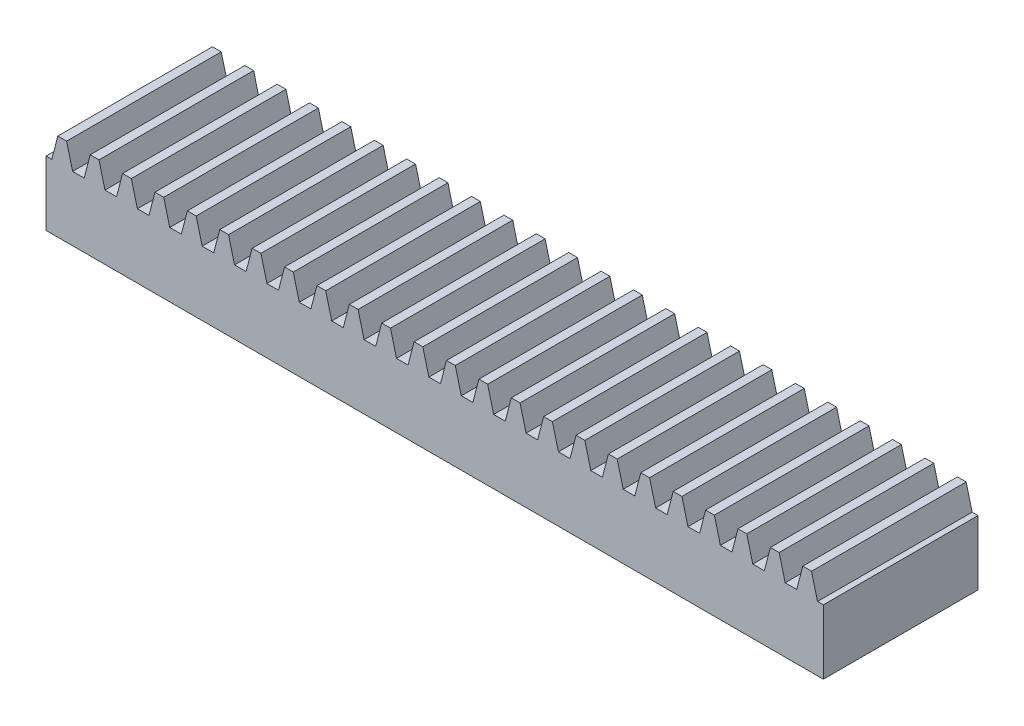
SolidWorks part; units mm, degrees
extrude "Blank" add sketch "BlankSke" against normal blind 30
sketch "BlankSke" plane through (0, 0, 0) normal (0, 0, 1) x (1, 0, 0)
  line L1 (0, 0) -> (150.8, 0)
  line L2 (0, 0) -> (0, 17)
  line L3 (0, 17) -> (150.8, 17)
  line L4 (150.8, 0) -> (150.8, 17)
  dimension "Length" = 150.8
  dimension "Blank_height" = 17
ref_plane "Plane1" through (0, 0, 0) normal (0, 0, 1) x (1, 0, 0)
ref_plane "Plane2" through (0, 0, 0) normal (0, 1, 0) x (1, 0, 0)
ref_plane "Plane3" through (0, 0, 0) normal (1, 0, 0) x (0, 0, -1)
sketch "HoldingSke" plane through (0, 0, 0) normal (0, 1, 0) x (1, 0, 0)
  line L0 (0, 0) -> (0.0696, 0.4951)
  line L1 (-15, 0) -> (100, 0) construction
  line L2 (0, 0) -> (-2.1039, 2.3779)
  line L3 (0, 0) -> (-11.863, 4.5341)
  line L4 (0, 0) -> (7.762, 3.7858)
  line L5 (0, 0) -> (-23.7986, -8.8762)
  line L6 (0, 0) -> (-10.5278, -7.1032)
  line L9 (-67.7845, 28.3722) -> (78.2121, 66.1296)
  line L10 (-76.2, 4.3779) -> (-61.2, 4.3779)
  line L11 (0, 0) -> (-30, 0)
  line L12 (-76.2, 101.6) -> (-76.133, 101.6)
  line L13 (24.9733, 27.94) -> (52.9518, 28.4284)
  line L14 (24.9733, 27.94) -> (24.9743, 27.94)
  line L15 (24.9733, 27.94) -> (100.4006, 29.5858)
  circle A0 centre (0, 0) radius 19.05
  circle A1 centre (0, 0) radius 7.5
  circle A2 centre (0, 0) radius 12.7
  dimension "MPH" = 15
  dimension "Diameter" = 38.1
  dimension "Num_teeth" = 26
  dimension "Pitch" = 0.5
  dimension "Show_teeth" = 998
  dimension "Thickness" = 12.7
  dimension "Ap" = 14.5
  dimension "Pitch_height" = 15
  dimension "Width" = 30
  dimension "Backlash" = 0.067
  dimension "Addendum_fac" = 1
  dimension "Dedendum_fac" = 1.25
  dimension "Clearance_fac" = 0.25
  dimension "Dedendum_add" = 0.001
  dimension "Length" = 150.8
  dimension "Module" = 2
sketch "TooCutSkeIll" plane through (0, 0, 0) normal (0, 0, 1) x (1, 0, 0)
  line L0 (-2.2735, 16.94) -> (-1.2224, 12.8756)
  line L1 (-0.7373, 12.5) -> (0.7373, 12.5)
  line L2 (1.2224, 12.8756) -> (2.2735, 16.94)
  line L3 (150.8, 17) -> (0, 17) construction
  line L4 (0, 0) -> (0, 64.897) construction
  line L5 (-13.208, 15) -> (12.954, 15) construction
  line L6 (0, 0) -> (150.8, 0) construction
  line L7 (1.7718, 15) -> (1.7718, 48.7463) construction
  line L8 (-1.7718, 15) -> (-1.7718, 48.7463) construction
  line L9 (2.351, 17) -> (2.351, 17.0254)
  line L10 (-2.351, 17) -> (-2.351, 17.0254)
  line L11 (-2.351, 17.0254) -> (2.351, 17.0254)
  arc A0 (0.7373, 12.5) -> (1.2224, 12.8756) centre (0.7373, 13.001) ccw
  arc A1 (-1.2224, 12.8756) -> (-0.7373, 12.5) centre (-0.7373, 13.001) ccw
  arc A2 (2.351, 17) -> (2.2735, 16.94) centre (2.351, 16.92) ccw
  arc A3 (-2.2735, 16.94) -> (-2.351, 17) centre (-2.351, 16.92) ccw
  dimension "Pitch_height" = 15
  dimension "Addendum_plus" = 2.0254
  dimension "Pressure_angle" = 14.5
  dimension "Gap_width" = 3.5436
  dimension "Dedendum" = 2.5
extrude "ToothCutIll" [suppressed] cut sketch "TooCutSkeIll" against normal through all
sketch "TooCutSkeSim" plane through (0, 0, 0) normal (0, 0, 1) x (1, 0, 0)
  line L0 (1.1253, 12.5) -> (-1.1253, 12.5)
  line L1 (2.2956, 17.0254) -> (1.1253, 12.5)
  line L2 (0, 17.4625) -> (0, 53.467) construction
  line L3 (2.2956, 17.0254) -> (-2.2956, 17.0254)
  line L6 (-2.2956, 17.0254) -> (-1.1253, 12.5)
  line L9 (-1.7718, 15) -> (1.7718, 15) construction
  line L10 (0, 0) -> (150.8, 0) construction
  line L11 (1.7718, 15) -> (1.7718, 53.467) construction
  line L12 (-1.7718, 15) -> (-1.7718, 53.467) construction
  dimension "Pitch_height" = 15
  dimension "Addendum_plus" = 2.0254
  dimension "Pressure_angle" = 14.5
  dimension "Gap_width" = 3.5436
  dimension "Dedendum" = 2.5
extrude "ToothCutSim" cut sketch "TooCutSkeSim" against normal through all
pattern_linear "TeethCuts" count 25 spacing 6.2832 along (1, 0, 0) of "ToothCutIll", "ToothCutSim"
equation "' \"Module@HoldingSke\" = 6.35"
equation "' \"Num_teeth@HoldingSke\" = 12"
equation "' \"Ap@HoldingSke\" =  20"
equation "' \"Ap@HoldingSke\" = 20"
equation "' \"Width@HoldingSke\" = 0.25 * 25.4"
equation "' \"Show_teeth@HoldingSke\" = 500"
equation "' \"Backlash@HoldingSke\" = 0.009 * 25.4"
equation "' \"Addendum_fac@HoldingSke\" = 1.0"
equation "' \"Dedendum_fac@HoldingSke\" = 1.25"
equation "' \"Dedendum_add@HoldingSke\" = 0.00005 * 25.4"
equation "' \"Clearance_fac@HoldingSke\" = 0.25"
equation "' \"Pitch_height@HoldingSke\" = 1 * 25.4"
equation "' \"Length@HoldingSke\" = 4.71 * 25.4"
equation "\"Pitch@HoldingSke\" = 1 / \"Module@HoldingSke\""
equation "\"MPH@HoldingSke\" = \"Dedendum_fac@HoldingSke\" / \"Pitch@HoldingSke\" + 2 * \"Dedendum_add@HoldingSke\" + 0.002 * 25.4"
equation "\"MPH@HoldingSke\" = ((sgn( \"MPH@HoldingSke\" - \"Pitch_height@HoldingSke\")+1)*( \"MPH@HoldingSke\" - \"Pitch_height@HoldingSke\"))/2 + \"Pitch_height@HoldingSke\""
equation "\"Blank_height@BlankSke\" = \"Pitch_height@HoldingSke\" + \"Addendum_fac@HoldingSke\"  / \"Pitch@HoldingSke\" "
equation "\"Length@BlankSke\" =  \"Length@HoldingSke\""
equation "\"Face_width@Blank\" = \"Width@HoldingSke\""
equation "\"Pressure_angle@TooCutSkeIll\" = \"Ap@HoldingSke\""
equation "\"Addendum_plus@TooCutSkeIll\" =  \"Addendum_fac@HoldingSke\"  / \"Pitch@HoldingSke\" + 0.001 *25.4"
equation "\"Dedendum@TooCutSkeIll\" = \"Dedendum_fac@HoldingSke\"  / \"Pitch@HoldingSke\""
equation "\"Pitch_height@TooCutSkeIll\" =  \"MPH@HoldingSke\""
equation "\"Gap_width@TooCutSkeIll\" = 3.14159265 / 2 / \"Pitch@HoldingSke\" + 6 * \"Backlash@HoldingSke\""
equation "\"Pressure_angle@TooCutSkeSim\" = \"Ap@HoldingSke\""
equation "\"Addendum_plus@TooCutSkeSim\" =  \"Addendum_fac@HoldingSke\"  / \"Pitch@HoldingSke\" + 0.001 * 25.4"
equation "\"Dedendum@TooCutSkeSim\" = \"Dedendum_fac@HoldingSke\"  / \"Pitch@HoldingSke\""
equation "\"Pitch_height@TooCutSkeSim\" =  \"MPH@HoldingSke\""
equation "\"Gap_width@TooCutSkeSim\" = 3.14159265 / 2 / \"Pitch@HoldingSke\" + 6 * \"Backlash@HoldingSke\""
equation "\"Root_fillet@TooCutSkeIll\" = \"Clearance_fac@HoldingSke\" / \"Pitch@HoldingSke\" + \"Dedendum_add@HoldingSke\""
equation "\"Break_rad@TooCutSkeIll\" = 0.02 / \"Pitch@HoldingSke\" * 2"
equation "\"Linear_pitch@TeethCuts\" = 3.14159265 / \"Pitch@HoldingSke\""
equation "\"Num_teeth@HoldingSke\" = int( ( \"Length@HoldingSke\" + 0 ) / (3.14159265 / \"Pitch@HoldingSke\")) + 0.9999  + 1"
equation " \"Num_teeth@TeethCuts\" = int( \"Show_teeth@HoldingSke\" ) + 1"
equation " \"Num_teeth@TeethCuts\" = ((sgn( \"Num_teeth@TeethCuts\" - \"Num_teeth@HoldingSke\" )-1)*( \"Num_teeth@TeethCuts\" - \"Num_teeth@HoldingSke\" ))/-2+ \"Num_teeth@HoldingSke\""
equation " \"Num_teeth@TeethCuts\" = ((sgn( \"Num_teeth@TeethCuts\" - 2.0)+1)*( \"Num_teeth@TeethCuts\" - 2.0))/2 +2.0"
